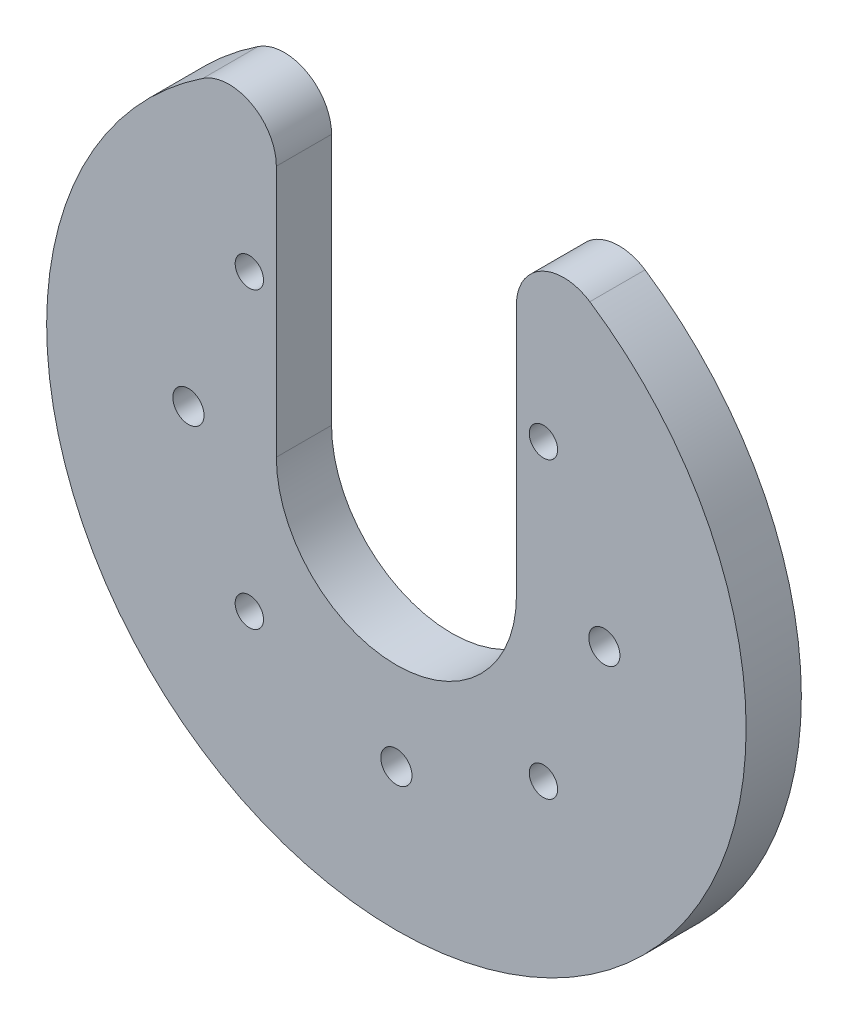
SolidWorks part; units mm, degrees
material "Beech"
ref_plane "Front Plane" through (0, 0, 0) normal (0, 0, 1) x (1, 0, 0)
ref_plane "Top Plane" through (0, 0, 0) normal (0, 1, 0) x (1, 0, 0)
ref_plane "Right Plane" through (0, 0, 0) normal (1, 0, 0) x (0, 0, -1)
sketch "Sketch1" plane through (0, 0, 0) normal (0, 0, 1) x (1, 0, 0)
  line L0 (0, 37) -> (0, -37) construction
  line L1 (-37, 0) -> (37, 0) construction
  line L2 (12.7, 0) -> (22, 0) construction
  line L4 (-12.7, 0) -> (-12.7, 34.7521)
  line L5 (12.7, 0) -> (12.7, 34.7521)
  arc A0 (-12.7, 34.7521) -> (12.7, 34.7521) centre (0, 0) ccw
  arc A1 (-12.7, 0) -> (12.7, 0) centre (0, 0) ccw
  circle A2 centre (22, 0) radius 1.65
  circle A3 centre (0, -22) radius 1.65
  circle A4 centre (-22, 0) radius 1.65
  circle A5 centre (0, 22) radius 1.65 [skipped]
  point P20 (0, 0)
  point P29 (0, 0)
  dimension "D1" = 74
  dimension "D2" = 25.4
  dimension "D4" = 3.3
  dimension "D3" = 22
  dimension "D5" = 4
extrude "Boss-Extrude1" add sketch "Sketch1" along normal blind 5.842
fillet "Fillet1" radius 5 2 edges at (12.7, 34.7521, 2.921) (-12.7, 34.7521, 2.921)
sketch "Sketch2" plane through (0, 0, 5.842) normal (0, 0, 1) x (1, 0, 0)
  line L0 (0, 0) -> (0, -22) construction
  line L2 (-15.5563, -15.5563) -> (0, 0) construction
  circle A0 centre (-15.5563, -15.5563) radius 1.5
  circle A1 centre (-15.5563, 15.5563) radius 1.5
  circle A2 centre (15.5563, 15.5563) radius 1.5
  circle A3 centre (15.5563, -15.5563) radius 1.5
  point P15 (0, 0)
  dimension "D2" = 3
  dimension "D1" = 45
  dimension "D3" = 4
extrude "Cut-Extrude1" cut sketch "Sketch2" against normal through all contours A1
